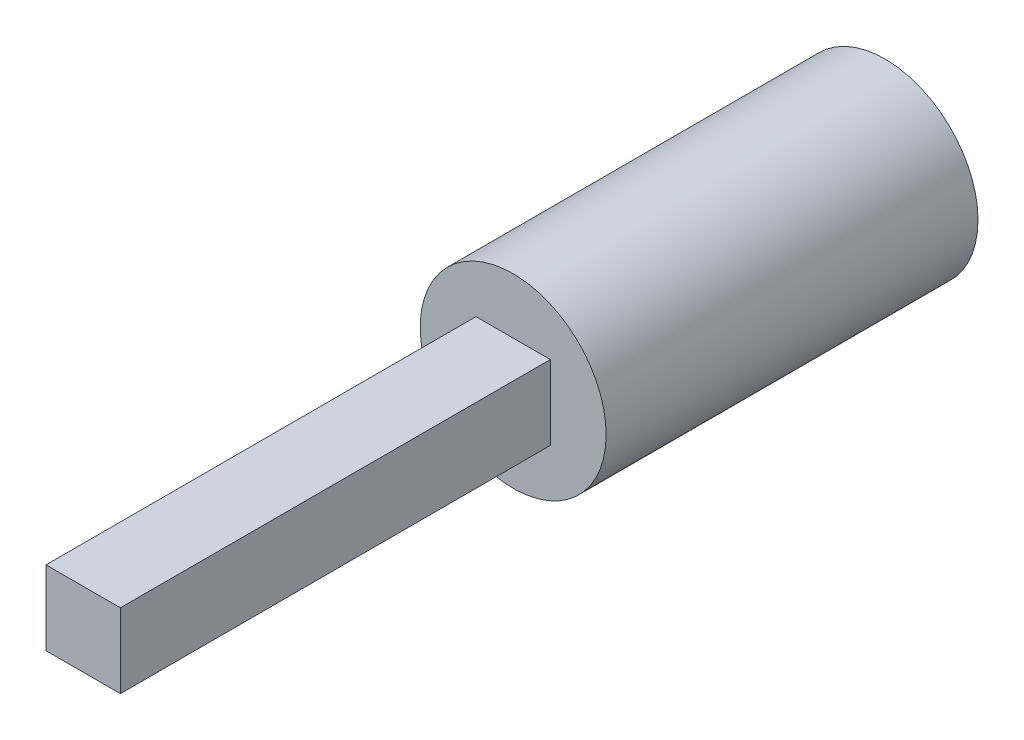
SolidWorks part; units mm, degrees
ref_plane "Front Plane" through (0, 0, 0) normal (0, 0, 1) x (1, 0, 0)
ref_plane "Top Plane" through (0, 0, 0) normal (0, 1, 0) x (1, 0, 0)
ref_plane "Right Plane" through (0, 0, 0) normal (1, 0, 0) x (0, 0, -1)
sketch "Sketch1" plane through (0, 0, 0) normal (0, 0, 1) x (1, 0, 0)
  circle A0 centre (0, 0) radius 4
  dimension "D1" = 8
extrude "Boss-Extrude1" add sketch "Sketch1" along normal blind 16
sketch "Sketch2" plane through (0, 0, 0) normal (0, 0, -1) x (-1, 0, 0)
  circle A0 centre (0, 0) radius 2.5
sketch "Sketch3" plane through (0, 0, 0) normal (0, 0, -1) x (-1, 0, 0)
  line L0 (-1.6583, -2.5) -> (1.6583, -2.5)
  arc A0 (1.6583, -2.5) -> (-1.6583, -2.5) centre (0, 0) ccw
  point P6 (0, -2.5)
extrude "Cut-Extrude3" cut sketch "Sketch3" against normal blind 14
sketch "Sketch6" plane through (0, 0, 16) normal (0, 0, 1) x (1, 0, 0)
  line L1 (-1.6, -1.6) -> (1.6, -1.6)
  line L2 (-1.6, -1.6) -> (-1.6, 1.6)
  line L3 (-1.6, 1.6) -> (1.6, 1.6)
  line L4 (1.6, -1.6) -> (1.6, 1.6)
  line L5 (-1.6, -1.6) -> (1.6, 1.6) construction
  line L6 (-1.6, 1.6) -> (1.6, -1.6) construction
  point P0 (0, 0)
  dimension "D1" = 3.2
  dimension "D2" = 3.2
extrude "Boss-Extrude2" add sketch "Sketch6" along normal blind 18.5
